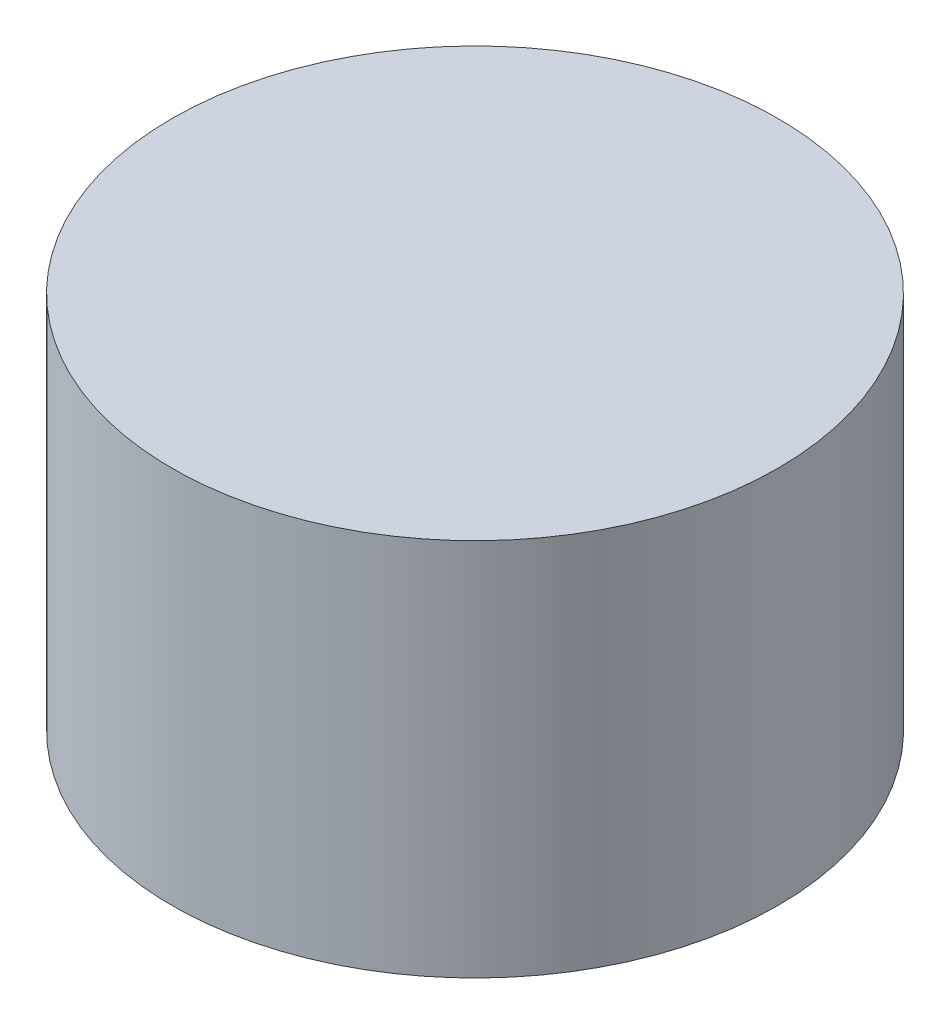
SolidWorks part; units mm, degrees
ref_plane "Front Plane" through (0, 0, 0) normal (0, 0, 1) x (1, 0, 0)
ref_plane "Top Plane" through (0, 0, 0) normal (0, 1, 0) x (1, 0, 0)
ref_plane "Right Plane" through (0, 0, 0) normal (1, 0, 0) x (0, 0, -1)
sketch "Sketch1" plane through (0, 0, 0) normal (0, 0, 1) x (1, 0, 0)
  line L0 (20, 25) -> (20, 0)
  line L1 (0, 20) -> (0, 0) construction
  line L5 (20, 0) -> (15, 0) construction
  line L6 (0, 20) -> (20, 20) construction
  line L7 (0, 0) -> (15, 0) construction
  line L12 (20, 25) -> (0, 25)
  line L13 (0, 25) -> (0, 20)
  line L14 (15, 0) -> (15, 25) construction
  line L17 (15, 0) -> (16.5, 0)
  line L18 (18.5, 0) -> (20, 0)
  arc A1 (18.5, 0) -> (16.5, 0) centre (17.5, 0) ccw
  conic Q0 (0, 20) -> (15, 0) control (15, 20) rho 0.3
  dimension "o ring radius" = 1
  dimension "Foam Thickness" = 5
  dimension "Egg Height/2" = 20
  dimension "egg max radius" = 15
revolve "Revolve1" add sketch "Sketch1" angle 360 about L1
